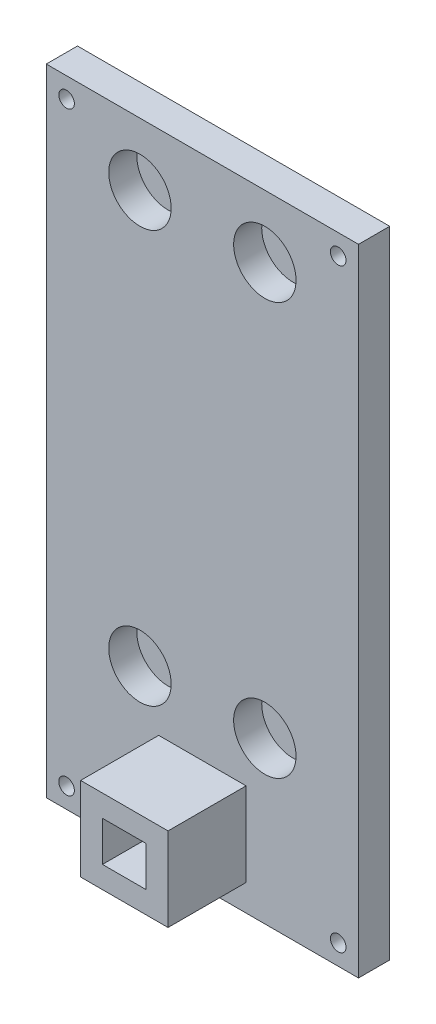
SolidWorks part; units mm, degrees
ref_plane "Plano frontal" through (0, 0, 0) normal (0, 0, 1) x (1, 0, 0)
ref_plane "Plano superior" through (0, 0, 0) normal (0, 1, 0) x (1, 0, 0)
ref_plane "Plano direito" through (0, 0, 0) normal (1, 0, 0) x (0, 0, -1)
sketch "Esboço1" plane through (0, 0, 0) normal (0, 0, 1) x (1, 0, 0)
  line L0 (0, 0) -> (100, 0)
  line L1 (100, 0) -> (100, 250)
  line L2 (100, 250) -> (0, 250)
  line L3 (0, 250) -> (0, 0)
  dimension "D1" = 100
  dimension "D2" = 250
extrude "Ressalto-extrusão1" add sketch "Esboço1" along normal blind 10
sketch "Esboço2" plane through (0, 0, 10) normal (0, 0, 1) x (1, 0, 0)
  line L0 (50, 0) -> (50, 250) construction
  line L1 (0, 0) -> (100, 0) construction
  line L2 (100, 250) -> (0, 250) construction
  line L3 (0, 55) -> (100, 55) construction
  line L4 (0, 250) -> (0, 0) construction
  line L5 (100, 0) -> (100, 250) construction
  line L6 (64, 55) -> (36, 55)
  line L7 (36, 55) -> (36, 81.8)
  line L8 (36, 81.8) -> (64, 81.8)
  line L9 (64, 55) -> (64, 81.8)
  line L10 (50, 62) -> (43, 62)
  line L11 (43, 62) -> (43, 74.8)
  line L12 (43, 74.8) -> (57, 74.8)
  line L13 (57, 62) -> (57, 74.8)
  line L14 (50, 62) -> (57, 62)
  point P17 (50, 81.8)
  point P18 (50, 55)
  point P20 (46.5, 62)
  point P24 (50, 74.8)
  dimension "D1" = 55
  dimension "D2" = 14
  dimension "D3" = 26.8
  dimension "D4" = 7
  dimension "D5" = 7
  dimension "D6" = 7
sketch "Esboço7" plane through (0, 0, 10) normal (0, 0, 1) x (1, 0, 0)
  line L0 (50, 250) -> (50, 0) construction
  line L1 (100, 250) -> (0, 250) construction
  line L2 (0, 0) -> (100, 0) construction
  circle A0 centre (30, 98) radius 10
  circle A1 centre (30, 230) radius 10
  circle A2 centre (70, 230) radius 10
  circle A3 centre (70, 98) radius 10
  dimension "D1" = 20
  dimension "D2" = 20
  dimension "D3" = 132
  dimension "D4" = 20
  dimension "D5" = 40
  dimension "D6" = 40
extrude "Corte-extrusão6" cut sketch "Esboço7" against normal blind 9
extrude "Ressalto-extrusão3" add sketch "Esboço2" along normal blind 25
sketch "Esboço8" plane through (0, 0, 10) normal (0, 0, 1) x (1, 0, 0)
  line L0 (43, 74.8) -> (45, 74.8)
  line L1 (57, 74.8) -> (43, 74.8) construction
  line L2 (45, 74.8) -> (45, 62)
  line L3 (43, 62) -> (57, 62) construction
  line L4 (45, 62) -> (43, 62)
  line L5 (43, 62) -> (43, 74.8)
  dimension "D1" = 2
extrude "Corte-extrusão7" cut sketch "Esboço8" against normal blind 10
sketch "Esboço9" plane through (0, 0, 0) normal (0, 0, -1) x (-1, 0, 0)
  line L0 (-43, 68.4) -> (0, 68.4) construction
  line L1 (-43, 74.8) -> (-43, 62) construction
  line L2 (0, 250) -> (0, 0) construction
  line L3 (-43, 69.9) -> (0, 69.9)
  line L4 (-43, 66.9) -> (0, 66.9)
  line L5 (-43, 69.9) -> (-43, 66.9)
  line L6 (0, 69.9) -> (0, 66.9)
  dimension "D1" = 1.5
  dimension "D2" = 1.5
extrude "Corte-extrusão8" cut sketch "Esboço9" against normal blind 2
sketch "Esboço10" plane through (0, 0, 10) normal (0, 0, 1) x (1, 0, 0)
  line L1 (0, 250) -> (0, 0) construction
  line L2 (100, 0) -> (100, 250) construction
  line L4 (0, 0) -> (100, 0) construction
  line L5 (100, 0) -> (0, 0)
  line L6 (0, 0) -> (0, 46.5)
  line L8 (0, 46.5) -> (100, 46.5)
  line L9 (100, 46.5) -> (100, 0)
  line L10 (36, 55) -> (64, 55) construction
  dimension "D1" = 8.5
extrude "Corte-extrusão9" cut sketch "Esboço10" against normal blind 12
sketch "Sketch1" plane through (0, 0, 10) normal (0, 0, 1) x (1, 0, 0)
  line L0 (0, 250) -> (0, 46.5) construction
  line L1 (100, 250) -> (0, 250) construction
  line L2 (100, 46.5) -> (100, 250) construction
  line L3 (100, 46.5) -> (0, 46.5) construction
  circle A0 centre (6.5, 243.5) radius 2.5
  circle A1 centre (93.5, 243.5) radius 2.5
  circle A2 centre (6.5, 53) radius 2.5
  circle A3 centre (93.5, 53) radius 2.5
  dimension "D1" = 5
  dimension "D4" = 5
  dimension "D7" = 5
  dimension "D8" = 5
  dimension "D11" = 6.5
  dimension "D12" = 6.5
  dimension "D2" = 6.5
  dimension "D3" = 6.5
  dimension "D5" = 6.5
  dimension "D6" = 6.5
  dimension "D9" = 6.5
  dimension "D10" = 6.5
extrude "Cut-Extrude1" cut sketch "Sketch1" against normal up to surface (10 mm away) up to face at (38.5, 95.0167, 0)
